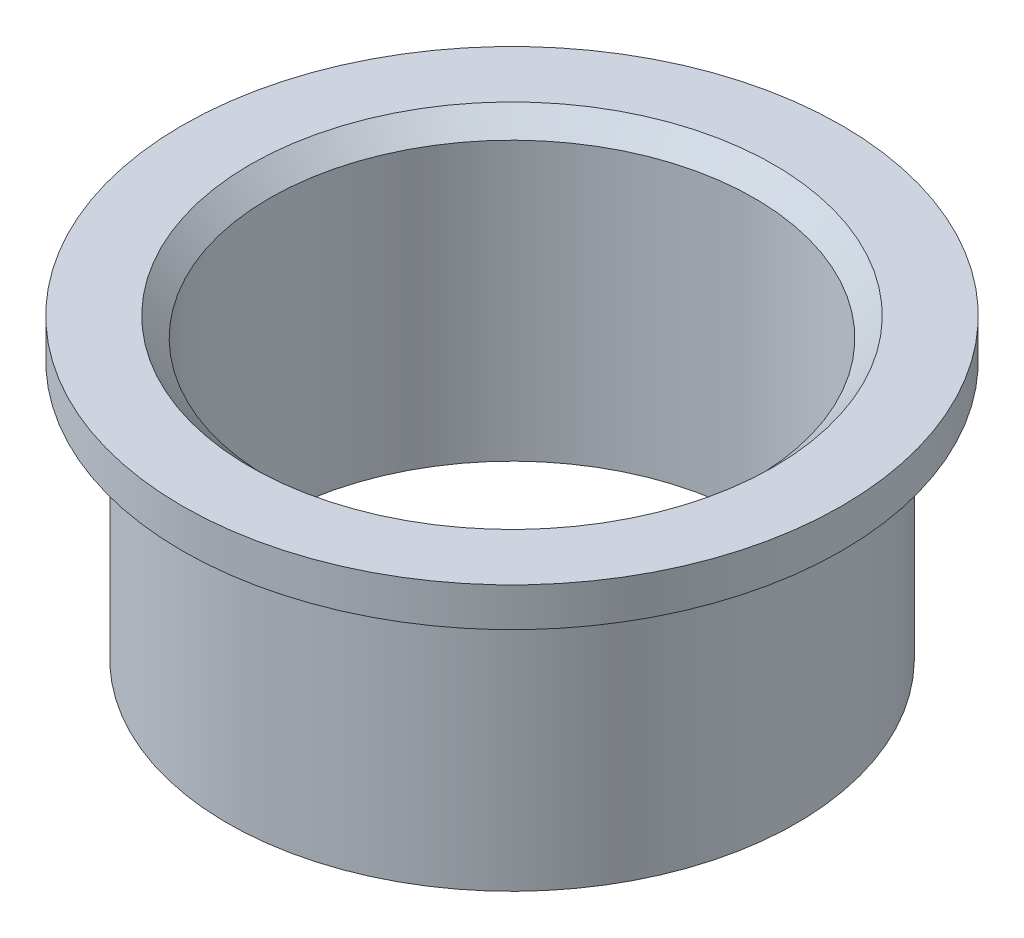
SolidWorks part; units mm, degrees
ref_plane "Front Plane" through (0, 0, 0) normal (0, 0, 1) x (1, 0, 0)
ref_plane "Top Plane" through (0, 0, 0) normal (0, 1, 0) x (1, 0, 0)
ref_plane "Right Plane" through (0, 0, 0) normal (1, 0, 0) x (0, 0, -1)
sketch "Sketch1" plane through (0, 0, 0) normal (0, 0, 1) x (1, 0, 0)
  line L0 (-51, 0) -> (-40.5, 0)
  line L1 (-40.5, 0) -> (-37.5, -3)
  line L2 (-37.5, -3) -> (-37.5, -46)
  line L3 (-37.5, -46) -> (-44, -46)
  line L4 (-44, -46) -> (-44, -6)
  line L5 (-44, -6) -> (-51, -6)
  line L6 (-51, -6) -> (-51, 0)
  line L7 (0, 0) -> (0, -75) construction
  point P3 (-44, 0)
  point P11 (-37.5, -8.0529)
  dimension "D1" = 102
  dimension "D2" = 88
  dimension "D3" = 75
  dimension "D4" = 45
  dimension "D5" = 3
  dimension "D6" = 6
  dimension "D7" = 40
revolve "Revolve1" add sketch "Sketch1" angle 360 about L7
